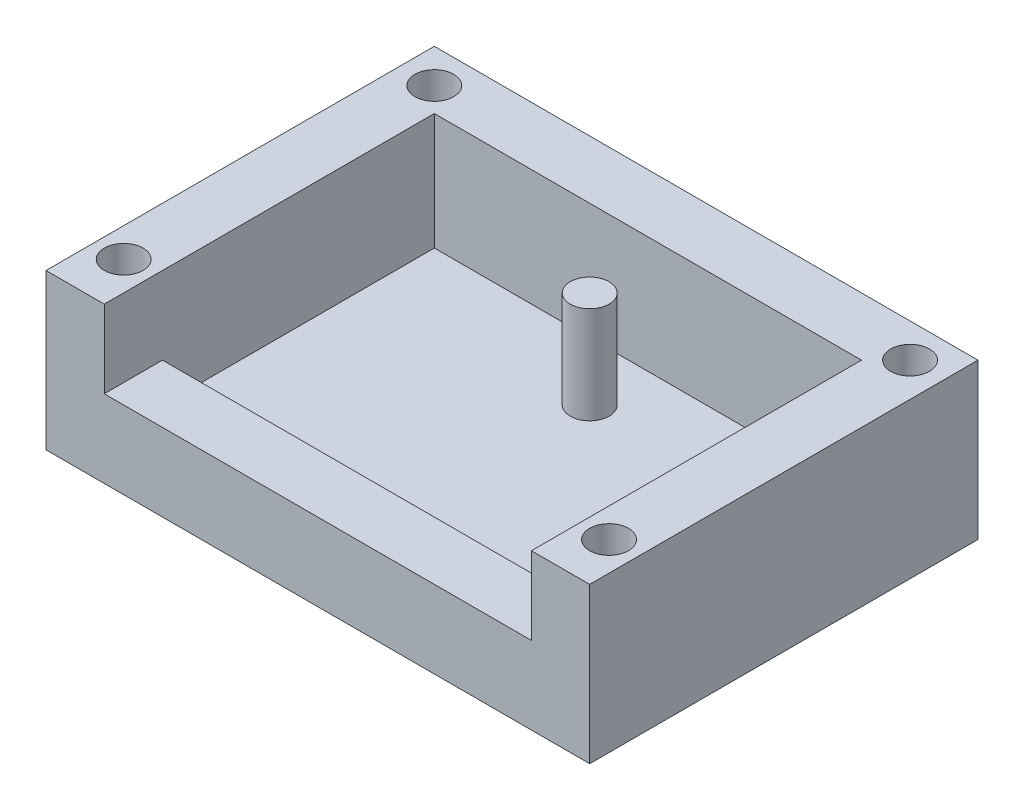
SolidWorks part; units mm, degrees
ref_plane "Plan de face" through (0, 0, 0) normal (0, 0, 1) x (1, 0, 0)
ref_plane "Plan de dessus" through (0, 0, 0) normal (0, 1, 0) x (1, 0, 0)
ref_plane "Plan de droite" through (0, 0, 0) normal (1, 0, 0) x (0, 0, -1)
sketch "Esquisse3" plane through (0, 0, 0) normal (0, 1, 0) x (1, 0, 0)
  line L1 (0, 0) -> (-28, 0)
  line L2 (0, 0) -> (0, -20)
  line L3 (0, -20) -> (-28, -20)
  line L4 (-28, 0) -> (-28, -20)
  dimension "D1" = 28
  dimension "D2" = 20
extrude "Boss.-Extru.1" add sketch "Esquisse3" along normal blind 8
sketch "Esquisse4" plane through (0, 8, 0) normal (0, 1, 0) x (1, 0, 0)
  line L8 (-3, -17) -> (-3, -3)
  line L9 (-3, -3) -> (-25, -3)
  line L10 (-25, -3) -> (-25, -17)
  line L11 (-25, -17) -> (-3, -17)
  line L12 (-3, -17) -> (-3, -3)
  line L13 (-3, -3) -> (-25, -3)
  line L14 (-25, -3) -> (-25, -17)
  line L15 (-25, -17) -> (-3, -17)
  dimension "D1" = 3
extrude "Enlèv. mat.-Extru.1" cut sketch "Esquisse4" against normal blind 6
sketch "Esquisse5" plane through (0, 8, 0) normal (0, 1, 0) x (1, 0, 0)
  line L0 (-28, -20) -> (0, -20) construction
  line L1 (-25, -17) -> (-3, -17)
  line L2 (-25, -17) -> (-25, -20)
  line L3 (-25, -20) -> (-3, -20)
  line L4 (-3, -17) -> (-3, -20)
  dimension "D1" = 22
extrude "Enlèv. mat.-Extru.2" cut sketch "Esquisse5" against normal blind 4
sketch "Esquisse7" plane through (0, 2, 0) normal (0, 1, 0) x (1, 0, 0)
  line L0 (-14, -20) -> (-14, -6) construction
  line L1 (-25, -20) -> (-3, -20) construction
  circle A1 centre (-14, -6) radius 1
  dimension "D2" = 2
  dimension "D1" = 14
extrude "Boss.-Extru.2" add sketch "Esquisse7" along normal blind 5
sketch "Esquisse9" plane through (0, 8, 0) normal (0, 1, 0) x (1, 0, 0)
  line L0 (0, 0) -> (-28, 0) construction
  line L2 (-28, 0) -> (-28, -20) construction
  circle A1 centre (-26.25, -1.75) radius 1
  dimension "D3" = 2
  dimension "D1" = 1.75
  dimension "D2" = 1.75
extrude "Enlèv. mat.-Extru.3" cut sketch "Esquisse9" against normal blind 2
ref_plane "coupe orthogonale par rapport a x" through (-14, 0, 0) normal (-1, 0, 0) x (0, 0, 1)
mirror "Symétrie1" about plane through (-14, 0, 0) normal (-1, 0, 0) of "Enlèv. mat.-Extru.3"
ref_plane "coupe orthogonale par rapport a z" through (0, 0, 10) normal (0, 0, -1) x (-1, 0, 0)
sketch "Esquisse11" plane through (0, 8, 0) normal (0, 1, 0) x (1, 0, 0)
  line L0 (-28, 0) -> (-28, -20) construction
  line L1 (-28, -20) -> (-25, -20) construction
  circle A0 centre (-26.5, -17.5) radius 1
  dimension "D1" = 2
  dimension "D2" = 1.5
  dimension "D3" = 2.5
extrude "Enlèv. mat.-Extru.4" cut sketch "Esquisse11" against normal blind 2
mirror "Symétrie2" about plane through (-14, 0, 0) normal (-1, 0, 0) of "Enlèv. mat.-Extru.4"
